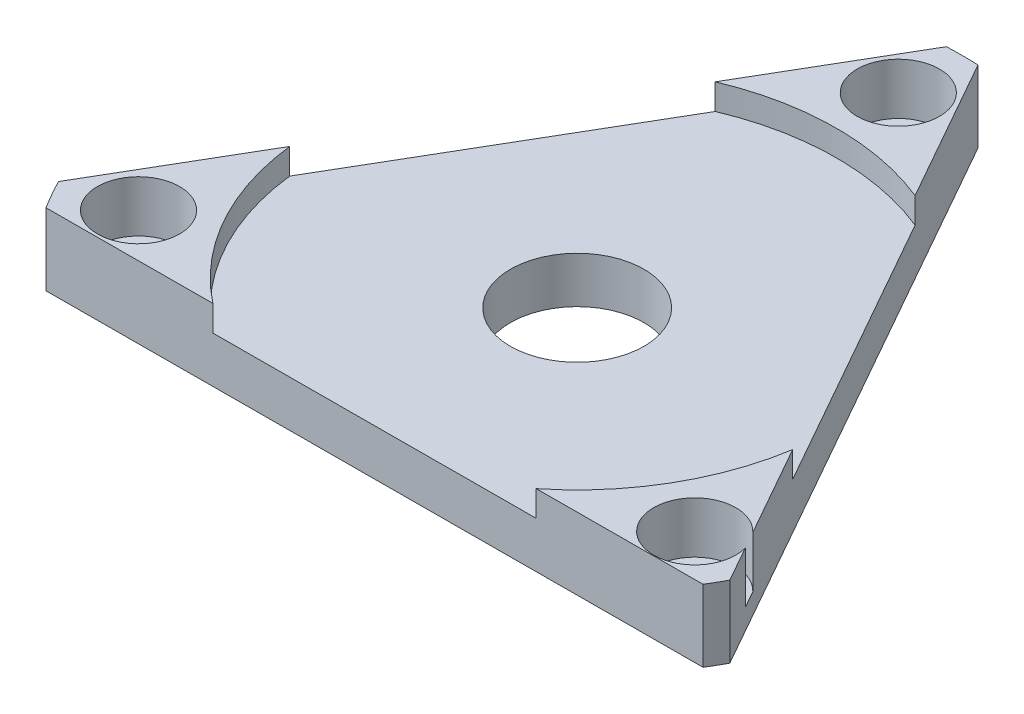
SolidWorks part; units mm, degrees
ref_plane "Front Plane" through (0, 0, 0) normal (0, 0, 1) x (1, 0, 0)
ref_plane "Top Plane" through (0, 0, 0) normal (0, 1, 0) x (1, 0, 0)
ref_plane "Right Plane" through (0, 0, 0) normal (1, 0, 0) x (0, 0, -1)
sketch "Sketch1" plane through (0, 0, 0) normal (0, 1, 0) x (1, 0, 0)
  circle A0 centre (0, 0) radius 75
  dimension "D1" = 150
extrude "Boss-Extrude1" add sketch "Sketch1" along normal blind 14
sketch "Sketch2" plane through (0, 14, 0) normal (0, 1, 0) x (1, 0, 0)
  circle A0 centre (0, 0) radius 13
  dimension "D1" = 26
sketch "Sketch4" plane through (0, 14, 0) normal (0, 1, 0) x (1, 0, 0)
  line L0 (0, 0) -> (0, 62.5) construction
  line L1 (0, 0) -> (54.1266, -31.25) construction
  line L2 (0, 0) -> (-54.1266, -31.25) construction
  circle A0 centre (0, 62.5) radius 5
  circle A1 centre (-54.1266, -31.25) radius 5
  circle A2 centre (54.1266, -31.25) radius 5
  circle A3 centre (0, 0) radius 62.5
  dimension "D1" = 10
  dimension "D2" = 10
  dimension "D3" = 10
  dimension "D4" = 62.5
  dimension "D5" = 120
extrude "Cut-Extrude4" cut sketch "Sketch4" against normal through all contours A3 A0 | A0 A3 | A2 A3 | A3 A2 | A3 A1 | A1 A3
extrude "Cut-Extrude5" cut sketch "Sketch2" against normal through all
sketch "Sketch5" plane through (0, 14, 0) normal (0, 1, 0) x (-1, 0, 0)
  circle A0 centre (0, 0) radius 50.5
  dimension "D1" = 101
extrude "Cut-Extrude6" cut sketch "Sketch5" against normal blind 5
sketch "Sketch6" plane through (0, 14, 0) normal (0, 1, 0) x (1, 0, 0)
  circle A0 centre (-54.1266, -31.25) radius 8
  circle A1 centre (0, 62.5) radius 8
  circle A2 centre (54.1266, -31.25) radius 8
  dimension "D1" = 16
  dimension "D2" = 16
  dimension "D3" = 16
extrude "Cut-Extrude7" cut sketch "Sketch6" against normal blind 10
sketch "Sketch7" plane through (0, 0, 0) normal (0, -1, 0) x (-1, 0, 0)
  line L0 (3.073, 74.937) -> (66.7511, -34.1949)
  line L1 (3.073, 74.937) -> (66.7511, -34.1949) construction
  line L2 (63.5451, -39.8375) -> (-63.8469, -39.352)
  line L3 (-21.8445, -38.9131) -> (-63.8469, -39.352) construction
  line L4 (-65.7628, -36.059) -> (-3.073, 74.937)
  line L5 (-3.073, 74.937) -> (-65.7628, -36.059) construction
  circle A0 centre (0, 0) radius 75 construction
  circle A1 centre (0, 0) radius 75
  circle M5 centre (0, 0) radius 75
extrude "Cut-Extrude8" cut sketch "Sketch7" against normal blind 17 contours L0 M5 | L2 M5 | L4 M5
